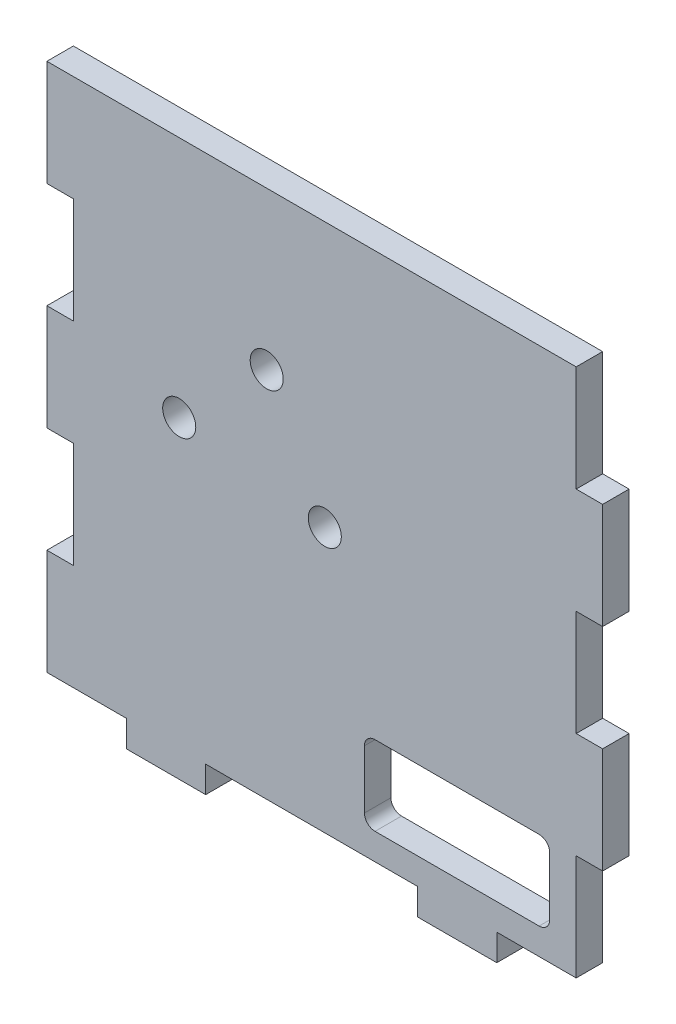
SolidWorks part; units mm, degrees
ref_plane "Front" through (0, 0, 0) normal (0, 0, 1) x (1, 0, 0)
ref_plane "Top" through (0, 0, 0) normal (0, 1, 0) x (1, 0, 0)
ref_plane "Right" through (0, 0, 0) normal (1, 0, 0) x (0, 0, -1)
sketch "Sketch1" plane through (0, 0, 0) normal (0, 0, 1) x (1, 0, 0)
  line L0 (-63.5, 38.1) -> (-63.5, 63.5)
  line L1 (-63.5, -63.5) -> (-44.45, -63.5)
  line L2 (-63.5, -63.5) -> (-63.5, -38.1)
  line L3 (-63.5, 63.5) -> (63.5, 63.5)
  line L4 (63.5, -63.5) -> (63.5, -38.1)
  line L5 (-63.5, -63.5) -> (63.5, 63.5) construction
  line L6 (-63.5, 63.5) -> (63.5, -63.5) construction
  line L7 (-63.5, 38.1) -> (-57.15, 38.1)
  line L8 (-63.5, -12.7) -> (-63.5, 12.7)
  line L9 (-63.5, 12.7) -> (-57.15, 12.7)
  line L10 (-57.15, 38.1) -> (-57.15, 12.7)
  line L11 (-63.5, -12.7) -> (-57.15, -12.7)
  line L12 (63.5, 38.1) -> (63.5, 63.5)
  line L13 (-63.5, -38.1) -> (-57.15, -38.1)
  line L14 (-57.15, -12.7) -> (-57.15, -38.1)
  line L15 (63.5, 38.1) -> (69.85, 38.1)
  line L16 (63.5, -12.7) -> (63.5, 12.7)
  line L17 (63.5, 12.7) -> (69.85, 12.7)
  line L18 (69.85, 38.1) -> (69.85, 12.7)
  line L19 (63.5, -12.7) -> (69.85, -12.7)
  line L20 (-25.4, -63.5) -> (25.4, -63.5)
  line L21 (63.5, -38.1) -> (69.85, -38.1)
  line L22 (69.85, -12.7) -> (69.85, -38.1)
  line L23 (44.45, -63.5) -> (63.5, -63.5)
  line L24 (-44.45, -63.5) -> (-44.45, -69.85)
  line L25 (-44.45, -69.85) -> (-25.4, -69.85)
  line L26 (-25.4, -63.5) -> (-25.4, -69.85)
  line L28 (25.4, -63.5) -> (25.4, -69.85)
  line L29 (25.4, -69.85) -> (44.45, -69.85)
  line L30 (44.45, -63.5) -> (44.45, -69.85)
  point P0 (0, 0)
  dimension "D1" = 127
  dimension "D2" = 127
  dimension "D3" = 6.35
  dimension "D4" = 25.4
  dimension "D5" = 25.4
  dimension "D6" = 25.4
  dimension "D7" = 6.35
  dimension "D8" = 19.05
  dimension "D9" = 19.05
  dimension "D10" = 19.05
extrude "BOXSIDE" add sketch "Sketch1" along normal blind 6.35 contours L3 L12 L15 L18 L17 L16 L19 L22 L21 L4 L23 L30 L29 L28 L20 L26 L25 L24 L1 L2 L13 L14 L11 L8 L9 L10 L7 L0
sketch "Sketch2" plane through (0, 0, 0) normal (0, 0, 1) x (1, 0, 0)
  line L0 (44.45, -63.5) -> (63.5, -63.5) construction
  line L2 (3.175, 0) -> (-10.7553, 25.7754) construction
  line L3 (-31.75, 5.3391) -> (-30.48, -19.05) construction
  line L6 (-63.5, -12.7) -> (-63.5, 12.7) construction
  line L7 (69.85, 38.1) -> (69.85, 12.7) construction
  line L8 (-10.7553, 25.7754) -> (-31.75, 5.3391) construction
  line L9 (-57.15, 38.1) -> (-57.15, 12.7) construction
  circle A0 centre (3.175, 0) radius 3.9688
  circle A1 centre (-30.48, -19.05) radius 3.9687 construction
  circle A2 centre (-31.75, 5.3391) radius 3.9688
  circle A3 centre (-10.7553, 25.7754) radius 3.9688
  dimension "D1" = 7.9375
  dimension "D2" = 44.45
  dimension "D3" = 33.02
  dimension "D4" = 24.4221
  dimension "D5" = 29.2989
  dimension "D6" = 66.675
  dimension "D7" = 29.2989
  dimension "D8" = 25.4
extrude "Cut-Extrude1" cut sketch "Sketch2" along normal through all contours A3 | A0 | A2
sketch "Sketch3" plane through (0, 0, 0) normal (0, 0, -1) x (-1, 0, 0)
  line L0 (-63.5, -63.5) -> (-63.5, -38.1) construction
  line L1 (-57.15, -38.1) -> (-12.7, -38.1)
  line L2 (-57.15, -38.1) -> (-57.15, -57.15)
  line L3 (-57.15, -57.15) -> (-12.7, -57.15)
  line L4 (-12.7, -38.1) -> (-12.7, -57.15)
  line L5 (-44.45, -63.5) -> (-63.5, -63.5) construction
  point P4 (-63.5, -50.8)
  dimension "D1" = 6.35
  dimension "D2" = 6.35
  dimension "D3" = 19.05
  dimension "D4" = 44.45
extrude "Cut-Extrude2" cut sketch "Sketch3" against normal through all
fillet "Fillet1" radius 2.54 4 edges at (12.7, -38.1, 3.175) (12.7, -57.15, 3.175) (57.15, -57.15, 3.175) (57.15, -38.1, 3.175)
